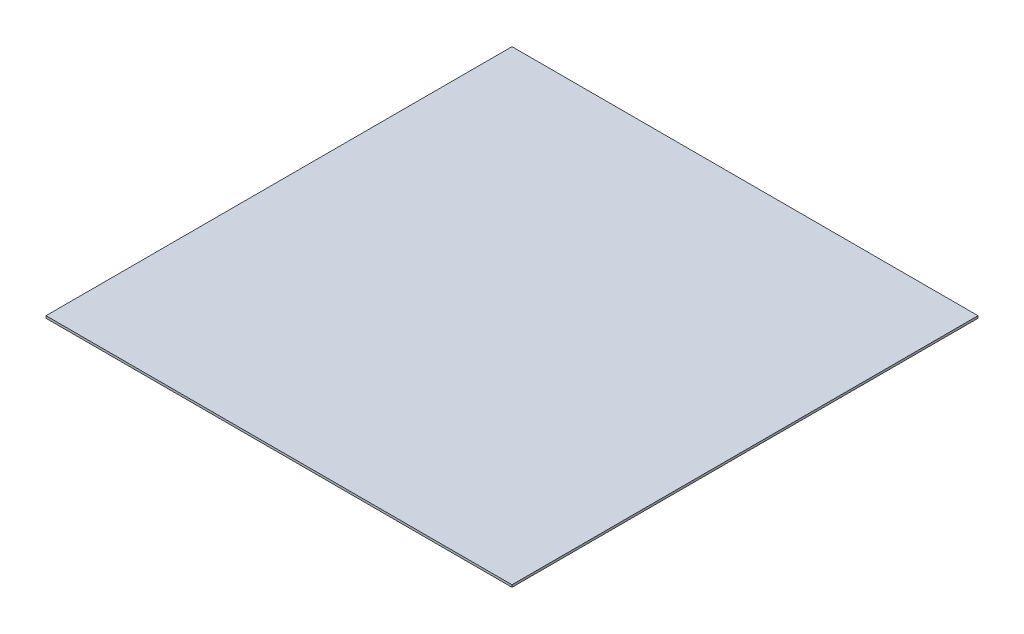
SolidWorks part; units mm, degrees
material "ABS PC"
ref_plane "前视基准面" through (0, 0, 0) normal (0, 0, 1) x (1, 0, 0)
ref_plane "上视基准面" through (0, 0, 0) normal (0, 1, 0) x (1, 0, 0)
ref_plane "右视基准面" through (0, 0, 0) normal (1, 0, 0) x (0, 0, -1)
sketch "草图1" plane through (0, 0, 0) normal (0, 1, 0) x (1, 0, 0)
  line L1 (-41, -41) -> (41, -41)
  line L2 (-41, -41) -> (-41, 41)
  line L3 (-41, 41) -> (41, 41)
  line L4 (41, -41) -> (41, 41)
  line L5 (-41, -41) -> (41, 41) construction
  line L6 (-41, 41) -> (41, -41) construction
  point P0 (0, 0)
  dimension "D1" = 82
  dimension "D2" = 82
extrude "凸台-拉伸1" add sketch "草图1" along normal blind 0.4
